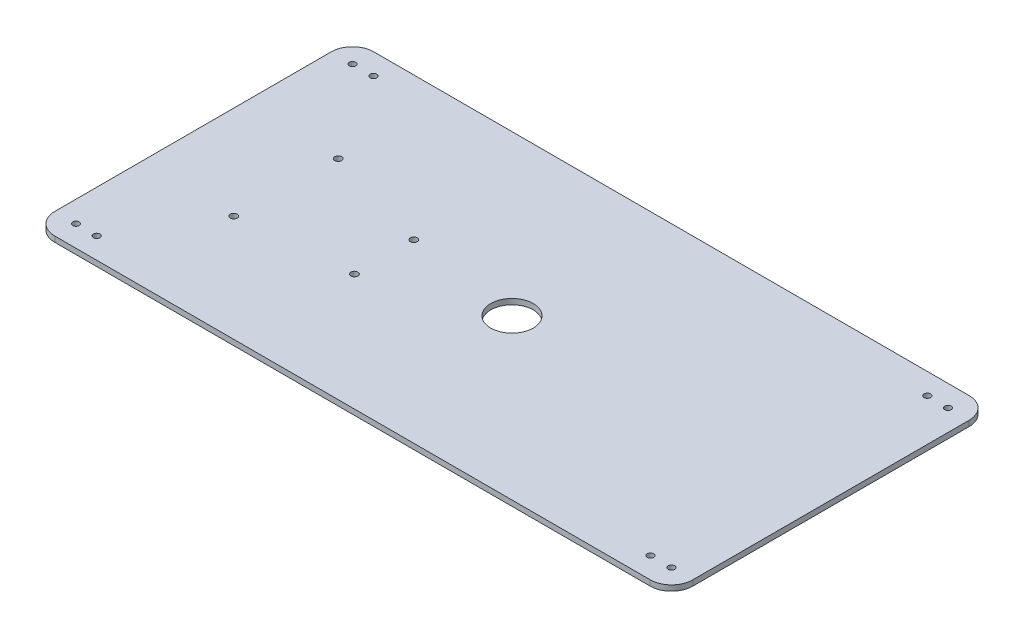
SolidWorks part; units mm, degrees
ref_plane "Front Plane" through (0, 0, 0) normal (0, 0, 1) x (1, 0, 0)
ref_plane "Top Plane" through (0, 0, 0) normal (0, 1, 0) x (1, 0, 0)
ref_plane "Right Plane" through (0, 0, 0) normal (1, 0, 0) x (0, 0, -1)
sketch "Sketch1" plane through (0, 0, 0) normal (0, 1, 0) x (1, 0, 0)
  line L1 (0, 0) -> (300, 0)
  line L2 (0, 0) -> (0, -150)
  line L3 (0, -150) -> (300, -150)
  line L4 (300, 0) -> (300, -150)
  dimension "D1" = 150
  dimension "D2" = 300
extrude "Boss-Extrude1" add sketch "Sketch1" along normal blind 2.6 contours L1 L4 L3 L2
fillet "Fillet1" radius 10 4 edges at (0, 1.3, 0) (0, 1.3, 150) (300, 1.3, 150) (300, 1.3, 0)
sketch "Sketch6" plane through (0, 0, 0) normal (0, -1, 0) x (1, 0, 0)
  line L0 (300, 10) -> (300, 140) construction
  line L1 (10, 0) -> (290, 0) construction
  circle A0 centre (290, 10) radius 1.5
  dimension "D1" = 3
  dimension "D2" = 10
  dimension "D3" = 10
ref_plane "Plane1" through (150, 0, 0) normal (1, 0, 0) x (0, 0, -1)
extrude "Cut-Extrude6" cut sketch "Sketch6" against normal blind 2.6 contours A0
ref_plane "Plane14" through (0, 0, 75) normal (0, 0, 1) x (1, 0, 0)
mirror "Mirror5" about plane through (150, 0, 0) normal (1, 0, 0) of "Cut-Extrude6"
mirror "Mirror6" about plane through (0, 0, 75) normal (0, 0, 1) of "Mirror5", "Cut-Extrude6"
sketch "Sketch15" plane through (0, 0, 0) normal (0, -1, 0) x (1, 0, 0)
  line L0 (150, 0) -> (150, 150) construction
  line L2 (0, 75) -> (300, 75) construction
  line L4 (0, 10) -> (0, 140) construction
  line L5 (300, 10) -> (300, 140) construction
  line L6 (10, 0) -> (290, 0) construction
  line L7 (10, 150) -> (290, 150) construction
  circle A0 centre (150, 75) radius 10
  dimension "D1" = 20
sketch "Sketch16" plane through (0, 2.6, 0) normal (0, 1, 0) x (1, 0, 0)
  circle A0 centre (45.1575, -51.8715) radius 1.6192
extrude "Cut-Extrude9" cut sketch "Sketch16" against normal blind 10
sketch "Sketch17" plane through (0, 2.6, 0) normal (0, 1, 0) x (1, 0, 0)
  circle A0 centre (95.9447, -67.1115) radius 1.6193
extrude "Cut-Extrude10" cut sketch "Sketch17" against normal through all
sketch "Sketch18" plane through (0, 2.6, 0) normal (0, 1, 0) x (1, 0, 0)
  circle A0 centre (44.0145, -99.7886) radius 1.6193
extrude "Cut-Extrude11" cut sketch "Sketch18" against normal through all
sketch "Sketch19" plane through (0, 2.6, 0) normal (0, 1, 0) x (1, 0, 0)
  circle A0 centre (95.9447, -95.0387) radius 1.6193
extrude "Cut-Extrude12" cut sketch "Sketch19" against normal through all
extrude "Cut-Extrude14" cut sketch "Sketch15" against normal through all contours A0
sketch "Sketch23" plane through (0, 2.6, 0) normal (0, 1, 0) x (1, 0, 0)
  circle A0 centre (19.812, -9.906) radius 1.524
extrude "Cut-Extrude15" cut sketch "Sketch23" against normal blind 2.6
mirror "Mirror7" about plane through (150, 0, 0) normal (1, 0, 0) of "Cut-Extrude15"
mirror "Mirror8" about plane through (0, 0, 75) normal (0, 0, 1) of "Mirror7", "Cut-Extrude15"
